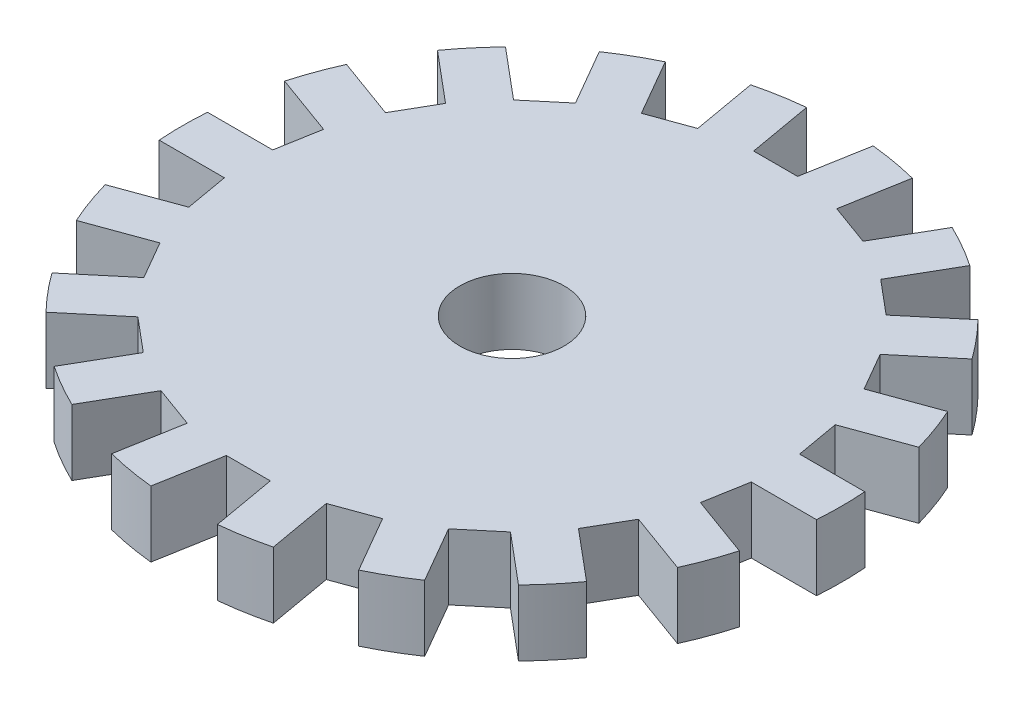
SolidWorks part; units mm, degrees
ref_plane "Спереди" through (0, 0, 0) normal (0, 0, 1) x (1, 0, 0)
ref_plane "Сверху" through (0, 0, 0) normal (0, 1, 0) x (1, 0, 0)
ref_plane "Справа" through (0, 0, 0) normal (1, 0, 0) x (0, 0, -1)
sketch "Эскиз1" plane through (0, 0, 0) normal (0, 1, 0) x (1, 0, 0)
  circle A0 centre (0, 0) radius 15
  dimension "D1" = 30
extrude "Бобышка-Вытянуть1" add sketch "Эскиз1" along normal blind 3
sketch "Эскиз2" plane through (0, 3, 0) normal (0, 1, 0) x (1, 0, 0)
  line L0 (0, 15) -> (0, 12)
  line L1 (1, 12) -> (-1, 12)
  line L2 (1, 12) -> (1.5154, 14.9233)
  line L3 (-1, 12) -> (-1.5154, 14.9233)
  circle A0 centre (0, 0) radius 15 construction
  arc A2 (1.5154, 14.9233) -> (-1.5154, 14.9233) centre (0, 0) ccw
  point P11 (0, 12)
  circle M5 centre (0, 0) radius 15
  dimension "D1" = 3
  dimension "D2" = 2
  dimension "D3" = 10
extrude "Вырез-Вытянуть1" cut sketch "Эскиз2" against normal blind 3 contours L1 L2 L0 M5 | L3 L1 L0 M5
pattern_circular "Круговой массив1" count 18 over 360 about axis through (0, 0, 0) along (0, 1, 0) of "Вырез-Вытянуть1"
sketch "Эскиз3" plane through (0, 3, 0) normal (0, 1, 0) x (1, 0, 0)
  circle A0 centre (0, 0) radius 2.375
  dimension "D1" = 4.75
extrude "Вырез-Вытянуть2" cut sketch "Эскиз3" against normal blind 10
sketch "Эскиз4" plane through (0, 3, 0) normal (0, 1, 0) x (1, 0, 0)
  line L0 (0, -5.0203) -> (0, 5.0203) construction
  circle A0 centre (5, 0) radius 0.75
  circle A1 centre (-5, 0) radius 0.75
  point P7 (0, 0)
  dimension "D2" = 1.5
  dimension "D1" = 5
extrude "Вырез-Вытянуть3" [suppressed] cut sketch "Эскиз4" against normal blind 10
